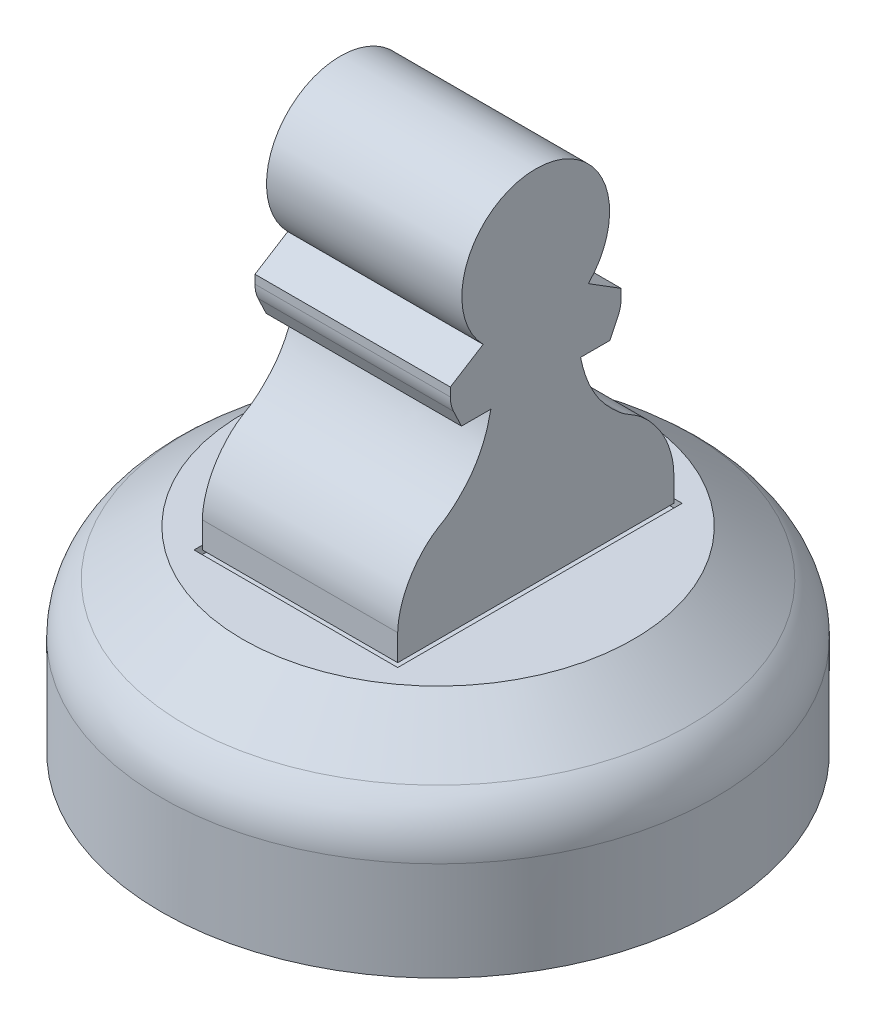
SolidWorks part; units mm, degrees
ref_plane "Front" through (0, 0, 0) normal (0, 0, 1) x (1, 0, 0)
ref_plane "Top" through (0, 0, 0) normal (0, 1, 0) x (1, 0, 0)
ref_plane "Right" through (0, 0, 0) normal (1, 0, 0) x (0, 0, -1)
sketch "Sketch1" plane through (0, 0, 0) normal (0, 1, 0) x (1, 0, 0)
  circle A0 centre (0, 0) radius 13.4938
  dimension "D1" = 26.9875
extrude "Boss-Extrude1" add sketch "Sketch1" along normal blind 6.35
sketch "Sketch2" plane through (0, 0, 0) normal (0, -1, 0) x (1, 0, 0)
  line L1 (-6.4516, -9.6266) -> (6.4516, -9.6266)
  line L2 (-6.4516, -9.6266) -> (-6.4516, 9.6266)
  line L3 (-6.4516, 9.6266) -> (6.4516, 9.6266)
  line L4 (6.4516, -9.6266) -> (6.4516, 9.6266)
  line L5 (-6.4516, -9.6266) -> (6.4516, 9.6266) construction
  line L6 (-6.4516, 9.6266) -> (6.4516, -9.6266) construction
  point P0 (0, 0)
  dimension "D1" = 19.2532
  dimension "D2" = 12.9032
extrude "Cut-Extrude1" cut sketch "Sketch2" against normal blind 4.7625
sketch "Sketch4" plane through (0, 0, 0) normal (0, 0, 1) x (1, 0, 0)
  line L0 (-13.4937, 6.35) -> (-9.525, 9.525)
  line L1 (-13.4937, 0) -> (13.4937, 0) construction
  line L2 (-9.525, 9.525) -> (0, 9.525)
  line L3 (0, 9.525) -> (0, 6.35)
  line L4 (13.4937, 6.35) -> (-13.4937, 6.35) construction
  line L5 (0, 6.35) -> (-13.4937, 6.35)
  dimension "D1" = 9.525
  dimension "D2" = 9.525
revolve "Revolve1" add sketch "Sketch4" angle 360 about L3
fillet "Fillet1" radius 3.175 1 edges at (0, 6.35, 13.4937)
sketch "Sketch5" plane through (0, 0, 0) normal (1, 0, 0) x (0, 0, -1)
  line L0 (29.9667, 135.239) -> (200.6333, 135.239) construction
  line L1 (-6.731, 9.525) -> (6.731, 9.525)
  line L2 (9.525, 9.525) -> (-9.525, 9.525) construction
  line L3 (-6.731, 9.525) -> (-6.731, 10.795)
  line L4 (6.731, 9.525) -> (6.731, 10.795)
  line L5 (-2.1852, 17.9599) -> (-3.6208, 17.9599)
  line L6 (-3.6208, 17.9599) -> (-4.1648, 19.1069)
  line L7 (-4.1648, 19.1069) -> (-4.1648, 19.884)
  line L8 (-4.1648, 19.884) -> (-2.5657, 20.8851)
  line L9 (-2.9767, 23.4136) -> (0, 23.4136) construction
  line L10 (0, 50) -> (0, -50) construction
  line L11 (2.1852, 17.9599) -> (3.6208, 17.9599)
  line L12 (3.6208, 17.9599) -> (4.1648, 19.1069)
  line L13 (4.1648, 19.1069) -> (4.1648, 19.884)
  line L14 (4.1648, 19.884) -> (2.5657, 20.8851)
  arc A0 (-2.5657, 20.8851) -> (2.5657, 20.8851) centre (0, 23.4136) cw
  spline S0 degree 3 poles (-6.731, 10.795) (-6.731, 11.0241) (-6.6496, 11.6027) (-6.3581, 12.4706) (-5.8084, 13.3301) (-5.2326, 13.9302) (-4.7356, 14.2672) (-4.3659, 14.467) (-3.9912, 14.7635) (-3.5856, 15.1524) (-3.1677, 15.621) (-2.8355, 16.138) (-2.4492, 16.9098) (-2.2732, 17.5317) (-2.1852, 17.9599) knots 0 0 0 0 0.078179 0.198071 0.309642 0.424068 0.47911 0.514035 0.56736 0.641472 0.705863 0.781201 0.850498 1 1 1 1
  spline S1 degree 3 poles (6.731, 10.795) (6.731, 11.0241) (6.6496, 11.6027) (6.3581, 12.4706) (5.8084, 13.3301) (5.2326, 13.9302) (4.7356, 14.2672) (4.3659, 14.467) (3.9912, 14.7635) (3.5856, 15.1524) (3.1677, 15.621) (2.8355, 16.138) (2.4492, 16.9098) (2.2732, 17.5317) (2.1852, 17.9599) knots 0 0 0 0 0.078179 0.198071 0.309642 0.424068 0.47911 0.514035 0.56736 0.641472 0.705863 0.781201 0.850498 1 1 1 1
  point P6 (0, 9.525)
  dimension "D1" = 13.462
  dimension "D2" = 1.27
extrude "Boss-Extrude2" add sketch "Sketch5" along normal mid plane 9.525 separate body
fillet "Fillet3" radius 1.5875 2 edges at (0, 19.1069, -4.1648) (0, 19.1069, 4.1648)
sketch "Sketch6" plane through (0, 9.525, 0) normal (0, 1, 0) x (1, 0, 0)
  line L16 (-4.9657, -6.9342) -> (4.9657, -6.9342)
  line L17 (-4.9657, 6.9342) -> (-4.9657, -6.9342)
  line L18 (4.9657, -6.9342) -> (4.9657, 6.9342)
  line L19 (4.9657, 6.9342) -> (-4.9657, 6.9342)
  line L20 (-4.9657, -6.9342) -> (4.9657, -6.9342)
  line L21 (-4.9657, 6.9342) -> (-4.9657, -6.9342)
  line L22 (4.9657, -6.9342) -> (4.9657, 6.9342)
  line L23 (4.9657, 6.9342) -> (-4.9657, 6.9342)
  dimension "D1" = 0.2032
extrude "Cut-Extrude2" cut sketch "Sketch6" against normal blind 0.3969
hole_wizard "#6 (0.204) Diameter Hole1" positions "Sketch8" profile "Sketch9" hole size "#6" standard "ANSI Inch" end condition through all
sketch "Sketch8" plane through (0, 4.7625, 0) normal (0, -1, 0) x (-1, 0, 0)
  point P0 (0, 0)
sketch "Sketch9" plane through (0, 4.7625, 0) normal (1, 0, 0) x (0, 0, -1)
  line L0 (0, 0) -> (0, 22.2534)
  line L1 (0, 22.2534) -> (2.5908, 22.2534)
  line L2 (2.5908, 22.2534) -> (2.5908, 0)
  line L5 (2.5908, 0) -> (0, 0)
  line L11 (0, -6.35) -> (0, 107.95) construction
  dimension "Thru Hole Dia." = 5.1816
  dimension "Thru Hole Depth" = 22.2534
